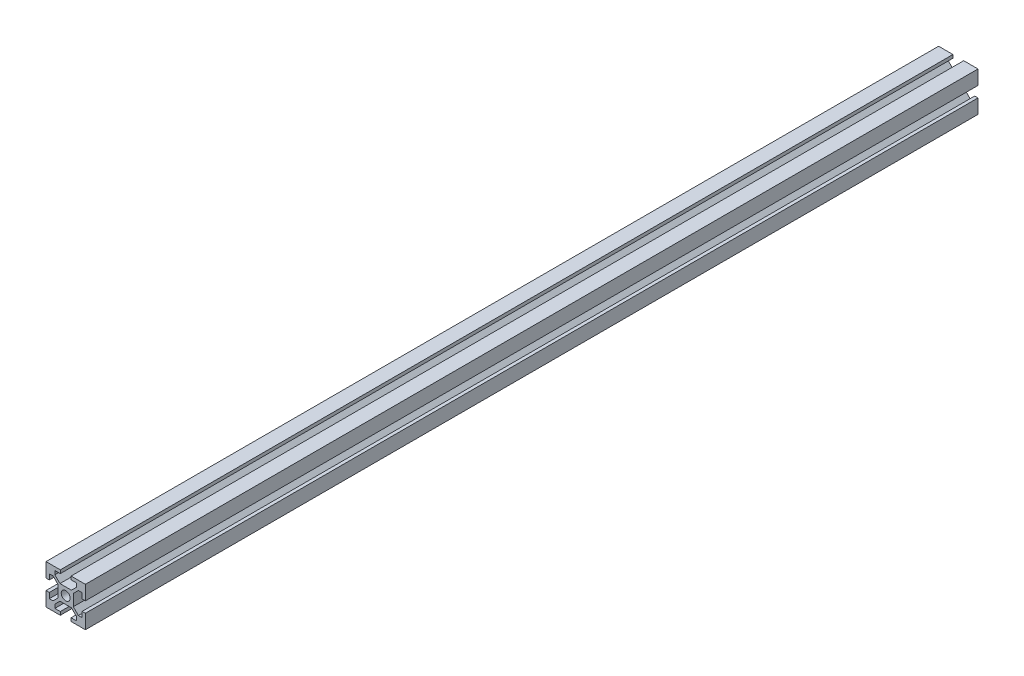
SolidWorks part; units mm, degrees
ref_plane "前视基准面" through (0, 0, 0) normal (0, 0, 1) x (1, 0, 0)
ref_plane "上视基准面" through (0, 0, 0) normal (0, 1, 0) x (1, 0, 0)
ref_plane "右视基准面" through (0, 0, 0) normal (1, 0, 0) x (0, 0, -1)
sketch "草图1" plane through (0, 0, 0) normal (0, 0, 1) x (1, 0, 0)
  line L0 (-4.1, 15) -> (-4.1, 12.5)
  line L1 (-4.3858, -5.8) -> (4.3858, -5.8)
  line L2 (-5.8, -4.3858) -> (-5.8, 4.3858)
  line L3 (-4.3858, 5.8) -> (4.3858, 5.8)
  line L4 (5.8, -4.3858) -> (5.8, 4.3858)
  line L5 (-9.6642, 8.25) -> (-12.5, 8.25)
  line L6 (-8.25, -12.5) -> (-4.1, -12.5)
  line L7 (-15, -15) -> (-4.1, -15)
  line L8 (-15, -15) -> (-15, -4.1)
  line L9 (-8.25, 15) -> (-4.1, 15)
  line L10 (15, -15) -> (15, -4.1)
  line L11 (-8.25, 9.6642) -> (-8.25, 12.5)
  line L12 (-8.25, 15) -> (-15, 15)
  line L13 (9.6642, 8.25) -> (12.5, 8.25)
  line L14 (8.25, 9.6642) -> (8.25, 12.5)
  line L15 (8.25, 15) -> (15, 15)
  line L16 (15, 8.25) -> (15, 15)
  line L17 (9.6642, -8.25) -> (12.5, -8.25)
  line L18 (8.25, -9.6642) -> (8.25, -12.5)
  line L19 (8.25, -15) -> (15, -15)
  line L20 (15, -8.25) -> (15, -15)
  line L21 (-15, 8.25) -> (-15, 15)
  line L22 (-9.6642, -8.25) -> (-12.5, -8.25)
  line L23 (-8.25, -9.6642) -> (-8.25, -12.5)
  line L24 (-8.25, -15) -> (-15, -15)
  line L25 (-15, -8.25) -> (-15, -15)
  line L26 (-12.5, -8.25) -> (-12.5, -4.1)
  line L27 (-8.25, 12.5) -> (-4.1, 12.5)
  line L28 (12.5, -8.25) -> (12.5, -4.1)
  line L29 (-8.25, 9.6642) -> (-4.3858, 5.8)
  line L30 (-9.6642, 8.25) -> (-5.8, 4.3858)
  line L31 (8.25, 9.6642) -> (4.3858, 5.8)
  line L32 (9.6642, 8.25) -> (5.8, 4.3858)
  line L33 (4.3858, -5.8) -> (8.25, -9.6642)
  line L34 (-5.8, -4.3858) -> (-9.6642, -8.25)
  line L35 (4.1, 15) -> (4.1, 12.5)
  line L36 (5.8, -4.3858) -> (9.6642, -8.25)
  line L37 (-4.3858, -5.8) -> (-8.25, -9.6642)
  line L38 (4.1, 15) -> (15, 15)
  line L39 (4.1, 12.5) -> (8.25, 12.5)
  line L40 (-4.1, -12.5) -> (-4.1, -15)
  line L41 (4.1, -15) -> (15, -15)
  line L42 (4.1, -12.5) -> (8.25, -12.5)
  line L43 (4.1, -12.5) -> (4.1, -15)
  line L44 (-15, 4.1) -> (-12.5, 4.1)
  line L45 (-15, -4.1) -> (-12.5, -4.1)
  line L46 (-15, 4.1) -> (-15, 15)
  line L47 (-12.5, 4.1) -> (-12.5, 8.25)
  line L48 (12.5, -4.1) -> (15, -4.1)
  line L49 (12.5, 4.1) -> (15, 4.1)
  line L50 (12.5, 4.1) -> (12.5, 8.25)
  line L51 (15, 4.1) -> (15, 15)
  line L52 (-15, 8.25) -> (-15, 4.1)
  line L53 (15, 8.25) -> (15, 4.1)
  line L54 (8.25, -15) -> (4.1, -15)
  line L55 (8.25, 15) -> (4.1, 15)
  circle A0 centre (0, 0) radius 3.4
extrude "凸台-拉伸1" add sketch "草图1" along normal blind 680 contours L49 L51 L16 L15 L38 L35 L39 L14 L31 L3 L29 L11 L27 L0 L9 L12 L21 L46 L44 L47 L5 L30 L2 L34 L22 L26 L45 L8 L7 L40 L6 L23 L37 L1 L33 L18 L42 L43 L41 L19 L10 L48 L28 L17 L36 L4 L32 L13
ref_plane "基准面1" through (0, 0, 340) normal (0, 0, 1) x (1, 0, 0)
